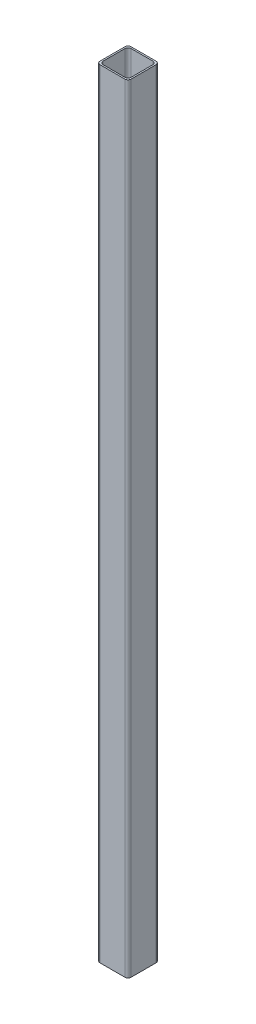
SolidWorks part; units mm, degrees
ref_plane "Front Plane" through (0, 0, 0) normal (0, 0, 1) x (1, 0, 0)
ref_plane "Top Plane" through (0, 0, 0) normal (0, 1, 0) x (1, 0, 0)
ref_plane "Right Plane" through (0, 0, 0) normal (1, 0, 0) x (0, 0, -1)
sketch "Sketch1" plane through (0, 0, 0) normal (0, 1, 0) x (1, 0, 0)
  line L0 (0, 39.3804) -> (0, -33.5382) construction
  line L1 (-16, -20) -> (16, -20)
  line L2 (-20, -16) -> (-20, 16)
  line L3 (-16, 20) -> (16, 20)
  line L4 (20, -16) -> (20, 16)
  line L5 (-20, -20) -> (20, 20) construction
  line L6 (-20, 20) -> (20, -20) construction
  line L7 (-14, -18) -> (14, -18)
  line L8 (-18, -14) -> (-18, 14)
  line L9 (-14, 18) -> (14, 18)
  line L10 (18, -14) -> (18, 14)
  line L11 (-18, -18) -> (18, 18) construction
  line L12 (-18, 18) -> (18, -18) construction
  line L13 (-37.6494, 0) -> (38.2985, 0) construction
  arc A0 (14, -18) -> (18, -14) centre (14, -14) ccw
  arc A1 (20, -16) -> (16, -20) centre (16, -16) cw
  arc A2 (-14, -18) -> (-18, -14) centre (-14, -14) cw
  arc A3 (-20, -16) -> (-16, -20) centre (-16, -16) ccw
  arc A4 (-18, 14) -> (-14, 18) centre (-14, 14) cw
  arc A5 (-16, 20) -> (-20, 16) centre (-16, 16) ccw
  arc A6 (18, 14) -> (14, 18) centre (14, 14) ccw
  arc A7 (16, 20) -> (20, 16) centre (16, 16) cw
  point P0 (0, 0)
  point P5 (0, 0)
  dimension "D5" = 4
  dimension "D1" = 2
  dimension "D2" = 40
  dimension "D3" = 2
  dimension "D4" = 40
extrude "Boss-Extrude1" add sketch "Sketch1" along normal mid plane 1000
